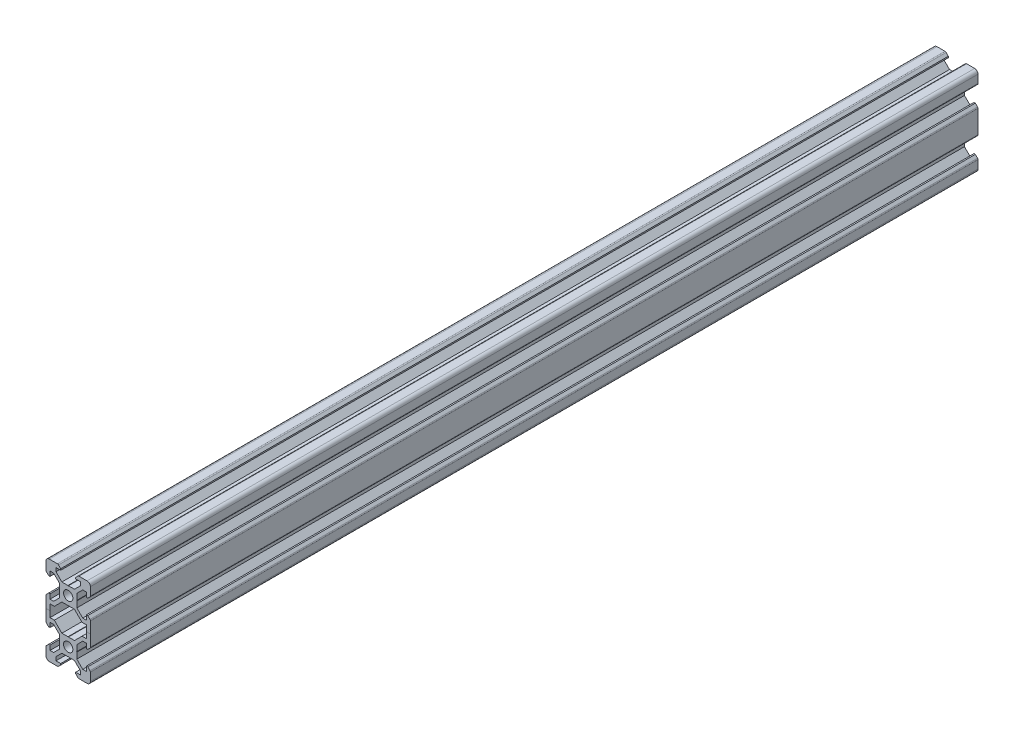
SolidWorks part; units mm, degrees
material "6063-T5"
ref_plane "Front" through (0, 0, 0) normal (0, 0, 1) x (1, 0, 0)
ref_plane "Top" through (0, 0, 0) normal (0, 1, 0) x (1, 0, 0)
ref_plane "Right" through (0, 0, 0) normal (1, 0, 0) x (0, 0, -1)
sketch "Sketch1" plane through (0, 0, 0) normal (0, 0, 1) x (1, 0, 0)
  line L0 (-8.5, 10) -> (-10, 8.5) construction
  line L1 (-8.5, 10) -> (-4.8628, 10)
  line L2 (-10, 8.5) -> (-10, 4.8628)
  line L4 (10, 8.5) -> (10, 4.8628)
  line L5 (-10, 10) -> (10, -10) construction
  line L6 (-10, -10) -> (10, 10) construction
  line L7 (8.2, -5.5) -> (8.2, -3.3865)
  line L8 (-8.2, -5.5) -> (-8.2, -3.3865)
  line L9 (-5.5, 8.2) -> (-3.3865, 8.2)
  line L10 (-8.2, -12.7) -> (-8.2, -7.3)
  line L11 (-3.9005, 2.8395) -> (-6.561, 5.5)
  line L12 (-6.561, 5.5) -> (-8.2, 5.5)
  line L13 (-2.8395, -3.9005) -> (-0.1, -3.9005)
  line L14 (-3.9005, -2.8395) -> (-3.9005, -0.1)
  line L15 (-2.8395, 3.9005) -> (-0.1, 3.9005)
  line L16 (3.9005, -2.8395) -> (3.9005, -0.1)
  line L17 (-8.2, 3.3865) -> (-8.81, 3.3865)
  line L18 (-8.81, 3.3865) -> (-9.7976, 4.3741)
  line L19 (8.5, 10) -> (10, 8.5) construction
  line L20 (-2.8395, 3.9005) -> (-5.5, 6.561)
  line L21 (-5.5, 6.561) -> (-5.5, 8.2)
  line L22 (-3.3865, 8.2) -> (-3.3865, 8.81)
  line L23 (-3.3865, 8.81) -> (-4.3741, 9.7976)
  line L24 (0, 24.069) -> (0, -33.8154) construction
  line L25 (3.3865, 8.81) -> (4.3741, 9.7976)
  line L26 (3.3865, 8.2) -> (3.3865, 8.81)
  line L27 (5.5, 6.561) -> (5.5, 8.2)
  line L28 (2.8395, 3.9005) -> (5.5, 6.561)
  line L29 (3.3865, 8.2) -> (5.5, 8.2)
  line L30 (4.8628, 10) -> (8.5, 10)
  line L31 (-0.1, 3.9005) -> (0, 3.8005)
  line L32 (0.1, 3.9005) -> (0, 3.8005)
  line L33 (0.1, 3.9005) -> (2.8395, 3.9005)
  line L34 (25.9287, 0) -> (-28.3459, 0) construction
  line L35 (-0.1, -3.9005) -> (0, -3.8005)
  line L36 (0.1, -3.9005) -> (0, -3.8005)
  line L37 (0.1, -3.9005) -> (2.8395, -3.9005)
  line L38 (-3.9005, 0.1) -> (-3.8005, 0)
  line L39 (-3.8005, 0) -> (-3.9005, -0.1)
  line L40 (-3.9005, 0.1) -> (-3.9005, 2.8395)
  line L41 (3.9005, 0.1) -> (3.8005, 0)
  line L42 (3.8005, 0) -> (3.9005, -0.1)
  line L43 (3.9005, 0.1) -> (3.9005, 2.8395)
  line L44 (8.81, 3.3865) -> (9.7976, 4.3741)
  line L45 (8.2, 3.3865) -> (8.81, 3.3865)
  line L46 (6.561, 5.5) -> (8.2, 5.5)
  line L47 (3.9005, 2.8395) -> (6.561, 5.5)
  line L48 (2.8395, -3.9005) -> (5.5, -6.561)
  line L49 (3.9005, -2.8395) -> (6.561, -5.5)
  line L50 (-2.8395, -3.9005) -> (-5.5, -6.561)
  line L51 (-3.9005, -2.8395) -> (-6.561, -5.5)
  line L52 (6.561, -5.5) -> (8.2, -5.5)
  line L53 (-6.561, -5.5) -> (-8.2, -5.5)
  line L54 (-8.81, -3.3865) -> (-9.7976, -4.3741)
  line L55 (-8.2, -3.3865) -> (-8.81, -3.3865)
  line L56 (8.81, -3.3865) -> (9.7976, -4.3741)
  line L57 (8.2, -3.3865) -> (8.81, -3.3865)
  line L58 (8.2, 3.3865) -> (8.2, 5.5)
  line L59 (10, -4.8628) -> (10, -15.1372)
  line L60 (-8.2, 3.3865) -> (-8.2, 5.5)
  line L61 (-10, -4.8628) -> (-10, -15.1372)
  line L62 (-28.3459, -10) -> (-10, -10) construction
  line L63 (-3.9005, -20.1) -> (-3.9005, -22.8395)
  line L64 (-3.9005, -20.1) -> (-3.8005, -20)
  line L65 (-3.8005, -20) -> (-3.9005, -19.9)
  line L66 (3.9005, -20.1) -> (3.9005, -22.8395)
  line L67 (3.9005, -20.1) -> (3.8005, -20)
  line L68 (3.8005, -20) -> (3.9005, -19.9)
  line L69 (6.561, -14.5) -> (8.2, -14.5)
  line L70 (3.9005, -17.1605) -> (6.561, -14.5)
  line L71 (3.9005, -17.1605) -> (3.9005, -19.9)
  line L72 (-3.9005, -17.1605) -> (-3.9005, -19.9)
  line L73 (-3.9005, -17.1605) -> (-6.561, -14.5)
  line L74 (-6.561, -14.5) -> (-8.2, -14.5)
  line L75 (-8.2, -16.6135) -> (-8.81, -16.6135)
  line L76 (-8.81, -16.6135) -> (-9.7976, -15.6259)
  line L77 (8.2, -16.6135) -> (8.81, -16.6135)
  line L78 (8.81, -16.6135) -> (9.7976, -15.6259)
  line L79 (-2.8395, -16.0995) -> (-5.5, -13.439)
  line L80 (-2.8395, -16.0995) -> (-0.1, -16.0995)
  line L81 (-0.1, -16.0995) -> (0, -16.1995)
  line L82 (0.1, -16.0995) -> (0, -16.1995)
  line L83 (0.1, -16.0995) -> (2.8395, -16.0995)
  line L84 (2.8395, -16.0995) -> (5.5, -13.439)
  line L85 (-8.2, -16.6135) -> (-8.2, -14.5)
  line L86 (8.2, -16.6135) -> (8.2, -14.5)
  line L87 (2.8395, -23.9005) -> (5.5, -26.561)
  line L88 (-2.8395, -23.9005) -> (-5.5, -26.561)
  line L89 (-0.1, -23.9005) -> (0, -23.8005)
  line L90 (0.1, -23.9005) -> (0, -23.8005)
  line L91 (0.1, -23.9005) -> (2.8395, -23.9005)
  line L92 (-2.8395, -23.9005) -> (-0.1, -23.9005)
  line L93 (-10, -28.5) -> (-10, -24.8628)
  line L94 (10, -28.5) -> (10, -24.8628)
  line L95 (8.81, -23.3865) -> (9.7976, -24.3741)
  line L96 (-8.81, -23.3865) -> (-9.7976, -24.3741)
  line L97 (-8.2, -23.3865) -> (-8.81, -23.3865)
  line L98 (8.2, -23.3865) -> (8.81, -23.3865)
  line L99 (8.2, -23.3865) -> (8.2, -25.5)
  line L100 (-8.2, -23.3865) -> (-8.2, -25.5)
  line L101 (-6.561, -25.5) -> (-8.2, -25.5)
  line L102 (6.561, -25.5) -> (8.2, -25.5)
  line L103 (3.9005, -22.8395) -> (6.561, -25.5)
  line L104 (-3.9005, -22.8395) -> (-6.561, -25.5)
  line L105 (-5.5, -28.2) -> (-3.3865, -28.2)
  line L106 (3.3865, -28.2) -> (5.5, -28.2)
  line L107 (3.3865, -28.2) -> (3.3865, -28.81)
  line L108 (3.3865, -28.81) -> (4.3741, -29.7976)
  line L109 (-3.3865, -28.2) -> (-3.3865, -28.81)
  line L110 (-3.3865, -28.81) -> (-4.3741, -29.7976)
  line L111 (-8.5, -30) -> (-4.8628, -30)
  line L112 (4.8628, -30) -> (8.5, -30)
  line L113 (-5.5, -26.561) -> (-5.5, -28.2)
  line L114 (5.5, -26.561) -> (5.5, -28.2)
  line L115 (-6.239, -7.3) -> (-8.2, -7.3)
  line L116 (-5.5, -6.561) -> (-6.239, -7.3)
  line L117 (6.239, -7.3) -> (8.2, -7.3)
  line L118 (5.5, -6.561) -> (6.239, -7.3)
  line L119 (-6.239, -12.7) -> (-8.2, -12.7)
  line L120 (-5.5, -13.439) -> (-6.239, -12.7)
  line L121 (5.5, -13.439) -> (6.239, -12.7)
  line L122 (6.239, -12.7) -> (8.2, -12.7)
  line L123 (8.2, -12.7) -> (8.2, -7.3)
  line L125 (10, -10) -> (25.9287, -10) construction
  circle A0 centre (0, 0) radius 2.1
  arc A1 (-8.5, 10) -> (-10, 8.5) centre (-8.5, 8.5) ccw
  arc A2 (10, 8.5) -> (8.5, 10) centre (8.5, 8.5) ccw
  arc A3 (-4.3741, 9.7976) -> (-4.8628, 10) centre (-4.8628, 9.3088) ccw
  arc A4 (4.8628, 10) -> (4.3741, 9.7976) centre (4.8628, 9.3088) ccw
  circle A5 centre (0, -20) radius 2.1
  arc A6 (9.7976, 4.3741) -> (10, 4.8628) centre (9.3088, 4.8628) ccw
  arc A7 (-10, 4.8628) -> (-9.7976, 4.3741) centre (-9.3088, 4.8628) ccw
  arc A8 (-10, -4.8628) -> (-9.7976, -4.3741) centre (-9.3088, -4.8628) cw
  arc A9 (9.7976, -4.3741) -> (10, -4.8628) centre (9.3088, -4.8628) cw
  arc A10 (-10, -15.1372) -> (-9.7976, -15.6259) centre (-9.3088, -15.1372) ccw
  arc A11 (9.7976, -15.6259) -> (10, -15.1372) centre (9.3088, -15.1372) ccw
  arc A12 (-10, -24.8628) -> (-9.7976, -24.3741) centre (-9.3088, -24.8628) cw
  arc A13 (9.7976, -24.3741) -> (10, -24.8628) centre (9.3088, -24.8628) cw
  arc A14 (4.8628, -30) -> (4.3741, -29.7976) centre (4.8628, -29.3088) cw
  arc A15 (-4.3741, -29.7976) -> (-4.8628, -30) centre (-4.8628, -29.3088) cw
  arc A16 (-8.5, -30) -> (-10, -28.5) centre (-8.5, -28.5) cw
  arc A17 (10, -28.5) -> (8.5, -30) centre (8.5, -28.5) cw
  point P17 (-9.25, 9.25)
  point P21 (9.25, 9.25)
  dimension "D2" = 4.2
  dimension "D4" = 1.5
  dimension "D3" = 20
  dimension "D5" = 0.529
  dimension "D6" = 6.773
  dimension "D7" = 90
  dimension "D8" = 11
  dimension "D9" = 0.61
  dimension "D10" = 0.1
  dimension "D11" = 0.1
  dimension "D12" = 0.1
  dimension "D13" = 0.1
  dimension "D14" = 5.679
  dimension "D15" = 1.639
  dimension "D16" = 1.8
  dimension "D17" = 90
  dimension "D18" = 6.773
  dimension "D19" = 90
  dimension "D20" = 20
  dimension "D21" = 1.8
extrude "Boss-Extrude2" add sketch "Sketch1" along normal blind 400
sketch "Sketch2" plane through (0, 0, 0) normal (0, 0, -1) x (-1, 0, 0)
  line L0 (-10, -10) -> (10, -10)
  line L1 (-10, -15.1372) -> (-10, -4.8628) construction
  line L2 (10, -4.8628) -> (10, -15.1372) construction
split line "SideFixture1 - SplitLine"
sketch "Sketch3" plane through (0, 0, 400) normal (0, 0, 1) x (1, 0, 0)
  line L0 (-10, -10) -> (10, -10)
  line L1 (-10, -4.8628) -> (-10, -15.1372) construction
  line L2 (10, -15.1372) -> (10, -4.8628) construction
split line "SideFixture2 - SplitLine"
sketch "Sketch4" plane through (0, 10, 0) normal (0, 1, 0) x (1, 0, 0)
  line L0 (-8.5, -200) -> (8.5, -200)
  line L1 (-8.5, -400) -> (-8.5, 0) construction
  line L2 (8.5, -400) -> (8.5, 0) construction
split line "SideFixture3 - SplitLine"
